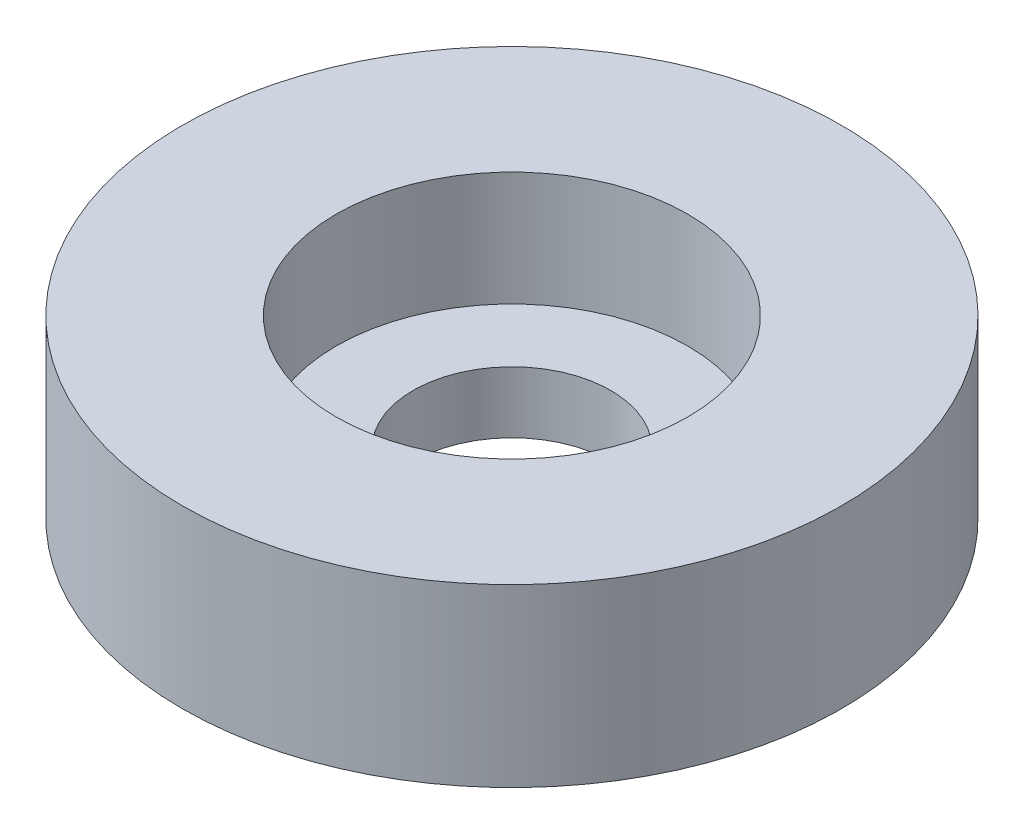
SolidWorks part; units mm, degrees
ref_plane "Plano frontal" through (0, 0, 0) normal (0, 0, 1) x (1, 0, 0)
ref_plane "Plano superior" through (0, 0, 0) normal (0, 1, 0) x (1, 0, 0)
ref_plane "Plano direito" through (0, 0, 0) normal (1, 0, 0) x (0, 0, -1)
sketch "Esboço1" plane through (0, 0, 0) normal (0, 1, 0) x (1, 0, 0)
  circle A0 centre (0, 0) radius 7.5
  dimension "D1" = 15
extrude "Ressalto-extrusão1" add sketch "Esboço1" along normal blind 4
hole_wizard "Rebaixo para parafuso com cabeça redonda de M41" positions "Esboço2" profile "Esboço4" counterbore size "M4" standard "ISO" end condition through all
sketch "Esboço2" plane through (0, 4, 0) normal (0, 1, 0) x (1, 0, 0)
  point P0 (0, 0)
sketch "Esboço4" plane through (0, 4, 0) normal (1, 0, 0) x (0, 0, 1)
  line L0 (0, 0) -> (0, 4)
  line L1 (0, 4) -> (2.25, 4)
  line L3 (2.25, 4) -> (2.25, 2.6)
  line L4 (2.25, 2.6) -> (4, 2.6)
  line L5 (4, 2.6) -> (4, 0)
  line L7 (4, 0) -> (0, 0)
  line L11 (0, -6.35) -> (0, 107.95) construction
  dimension "Thru Hole Dia." = 4.5
  dimension "Thru Hole Depth" = 4
  dimension "C'Bore Dia." = 8
  dimension "C'Bore Depth" = 2.6
